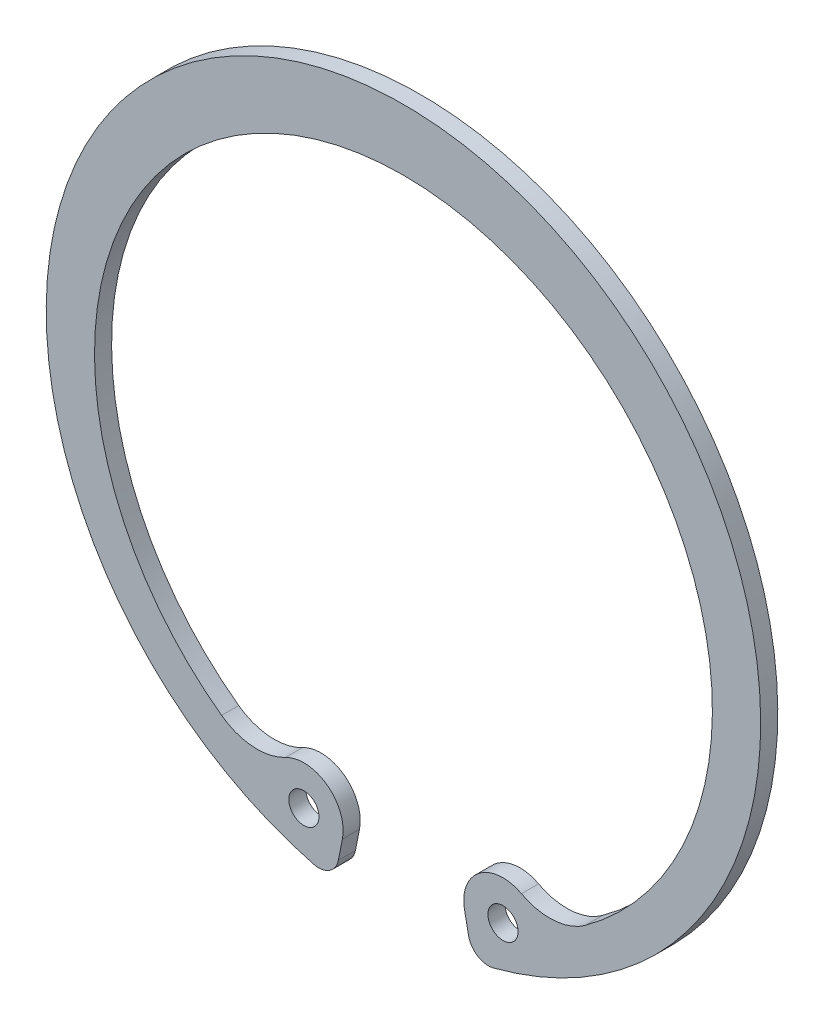
SolidWorks part; units mm, degrees
material "AISI 1020"
ref_plane "Спереди" through (0, 0, 0) normal (0, 0, 1) x (1, 0, 0)
ref_plane "Сверху" through (0, 0, 0) normal (0, 1, 0) x (1, 0, 0)
ref_plane "Справа" through (0, 0, 0) normal (1, 0, 0) x (0, 0, -1)
sketch "Эскиз1" plane through (0, 0, 0) normal (0, 0, 1) x (1, 0, 0)
  line L0 (0, -1000) -> (0, 49000) construction
  line L1 (0, 0) -> (11.9, -30.0818) construction
  line L2 (8.1269, -31.0687) -> (8.6527, -33.0786)
  line L3 (0, 30.15) -> (62.9, 30.15) construction
  arc A0 (11.2058, -34.4745) -> (0, 36.25) centre (0, 0) ccw
  circle A2 centre (11.9, -30.0818) radius 1.5
  arc A3 (13.5216, -26.5349) -> (8.1269, -31.0687) centre (11.9, -30.0818) ccw
  arc A4 (13.5216, -26.5349) -> (19.7924, -25.741) centre (16.0165, -21.0782) ccw
  arc A5 (8.6527, -33.0786) -> (11.2058, -34.4745) centre (10.5876, -32.5725) ccw
  arc A6 (19.7924, -25.741) -> (0, 30.15) centre (0, -1.3) ccw
  dimension "_d2" = 72.5
  dimension "_d4" = 3
  dimension "_r1" = 6
  dimension "_r2" = 2
  dimension "D1" = 31.45
  dimension "_e" = 1.3
  dimension "_a" = 7.8
  dimension "_l" = 16
  dimension "_d3" = 62.9
sketch "Эскиз2" plane through (0, 0, 0) normal (0, 0, 1) x (1, 0, 0)
  line L0 (0, -201000) -> (0, 249000) construction
  line L1 (-6.4737, -32.8103) -> (-6.0689, -30.7726)
  line L2 (8.1269, -31.0687) -> (8.6527, -33.0786) construction
  line L3 (0, 0) -> (11.2058, -34.4745) construction
  line L4 (0, 0) -> (-8.939, -34.3561) construction
  line L5 (8.6527, -33.0786) -> (11.2058, -34.4745) construction
  line L6 (-8.939, -34.3561) -> (-6.4737, -32.8103) construction
  line L7 (13.5216, -26.5349) -> (8.1269, -31.0687) construction
  line L8 (-11.7246, -26.5689) -> (-6.0689, -30.7726) construction
  line L9 (0, 35.5) -> (0, 37.2) construction
  circle A0 centre (0, 0) radius 35.5 construction
  circle A1 centre (0, 0) radius 34 construction
  circle A2 centre (0, 0) radius 25.7 construction
  arc A3 (0, 35.5) -> (-8.939, -34.3561) centre (0, 0) ccw
  arc A4 (0, 29.4) -> (-18.0726, -26.1212) centre (0, -1.302) ccw
  arc A5 (-8.939, -34.3561) -> (-6.4737, -32.8103) centre (-8.4354, -32.4206) ccw
  arc A6 (-6.0689, -30.7726) -> (-11.7246, -26.5689) centre (-9.8941, -30.0127) ccw
  arc A7 (8.6527, -33.0786) -> (11.2058, -34.4745) centre (10.5876, -32.5725) ccw construction
  arc A8 (13.5216, -26.5349) -> (8.1269, -31.0687) centre (11.9, -30.0818) ccw construction
  arc A9 (-18.0726, -26.1212) -> (-11.7246, -26.5689) centre (-14.5407, -21.2709) ccw
  circle A10 centre (-9.8941, -30.0127) radius 1.5
  circle A11 centre (11.9, -30.0818) radius 1.5 construction
  arc A13 (13.5216, -26.5349) -> (19.7924, -25.741) centre (16.0165, -21.0782) ccw construction
  dimension "_D" = 68
  dimension "_d1" = 71
  dimension "_DD" = 51.4
  dimension "_b" = 6.1
  dimension "D1" = 161.993
  dimension "D2" = 36.25
  dimension "D3" = 165.416
  dimension "_s" = 1.7
sketch "Эскиз3" plane through (0, 0, 0) normal (0, 0, 1) x (1, 0, 0)
  line L0 (-6.4737, -32.8103) -> (-6.0689, -30.7726) construction
  line L1 (-6.4737, -32.8103) -> (-6.0689, -30.7726)
  line L2 (0, -1000) -> (0, 49000) construction
  line L3 (0, -1000.0733) -> (0, 48999.9267) construction
  line L4 (6.4737, -32.8103) -> (6.0689, -30.7726)
  arc A0 (0, 29.4) -> (-18.0726, -26.1212) centre (0, -1.302) ccw construction
  arc A1 (-18.0726, -26.1212) -> (-11.7246, -26.5689) centre (-14.5407, -21.2709) ccw construction
  arc A2 (-6.0689, -30.7726) -> (-11.7246, -26.5689) centre (-9.8941, -30.0127) ccw construction
  arc A3 (-8.939, -34.3561) -> (-6.4737, -32.8103) centre (-8.4354, -32.4206) ccw construction
  arc A4 (0, 35.5) -> (-8.939, -34.3561) centre (0, 0) ccw construction
  arc A5 (18.0726, -26.1212) -> (-18.0726, -26.1212) centre (0, -1.302) ccw
  arc A6 (-18.0726, -26.1212) -> (-11.7246, -26.5689) centre (-14.5407, -21.2709) ccw
  arc A7 (-6.0689, -30.7726) -> (-11.7246, -26.5689) centre (-9.8941, -30.0127) ccw
  arc A8 (-8.939, -34.3561) -> (-6.4737, -32.8103) centre (-8.4354, -32.4206) ccw
  arc A9 (8.939, -34.3561) -> (-8.939, -34.3561) centre (0, 0) ccw
  circle A10 centre (-9.8941, -30.0127) radius 1.5 construction
  circle A11 centre (-9.8941, -30.0127) radius 1.5
  circle A12 centre (9.8941, -30.0127) radius 1.5
  arc A13 (18.0726, -26.1212) -> (11.7246, -26.5689) centre (14.5407, -21.2709) cw
  arc A14 (6.0689, -30.7726) -> (11.7246, -26.5689) centre (9.8941, -30.0127) cw
  arc A15 (8.939, -34.3561) -> (6.4737, -32.8103) centre (8.4354, -32.4206) cw
extrude "Бобышка-Вытянуть1" add sketch "Эскиз3" along normal blind 1.7
equation "\"D1@Эскиз1\"=\"_d3@Эскиз1\"/2"
equation "\"D3@Эскиз2\"=(\"D2@Эскиз2\"*2*\"D1@Эскиз2\"/360)/(\"_d1@Эскиз2\"/360)"
equation "\"D1@Бобышка-Вытянуть1\"= \"_s@Эскиз2\""
